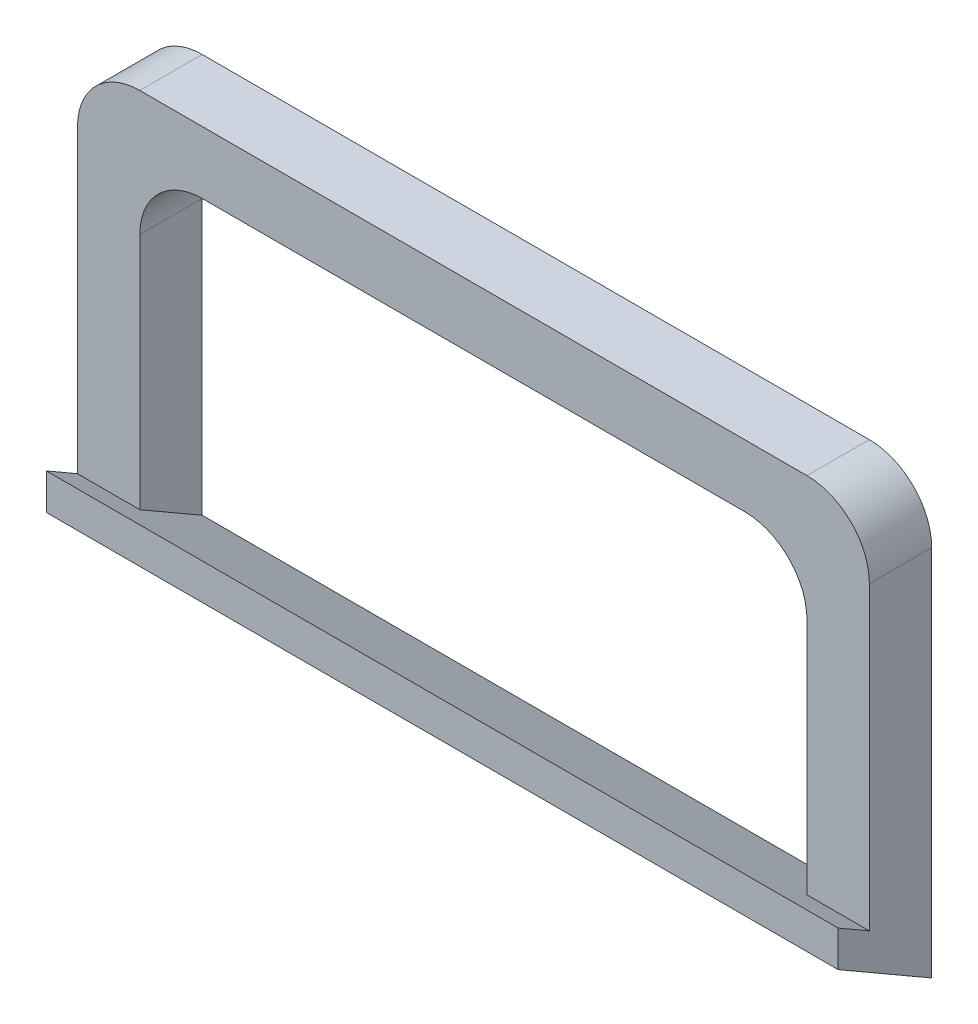
SolidWorks part; units mm, degrees
ref_plane "Alzado" through (0, 0, 0) normal (0, 0, 1) x (1, 0, 0)
ref_plane "Planta" through (0, 0, 0) normal (0, 1, 0) x (1, 0, 0)
ref_plane "Vista lateral" through (0, 0, 0) normal (1, 0, 0) x (0, 0, -1)
sketch "Croquis1" plane through (0, 0, 0) normal (0, 0, 1) x (1, 0, 0)
  line L0 (-36.9312, -5.2517) -> (-36.9312, 48.7483)
  line L1 (-26.9312, 58.7483) -> (80.0688, 58.7483)
  line L2 (90.0688, 48.7483) -> (90.0688, -5.2517)
  line L3 (-36.9312, -5.2517) -> (-26.9312, -5.2517)
  line L4 (-26.9312, -5.2517) -> (-26.9312, 38.7483)
  line L5 (-16.9312, 48.7483) -> (70.0688, 48.7483)
  line L6 (80.0688, 38.7483) -> (80.0688, -5.2517)
  line L7 (80.0688, -5.2517) -> (90.0688, -5.2517)
  arc A0 (-26.9312, 58.7483) -> (-36.9312, 48.7483) centre (-26.9312, 48.7483) ccw
  arc A1 (80.0688, 58.7483) -> (90.0688, 48.7483) centre (80.0688, 48.7483) cw
  arc A2 (-26.9312, 38.7483) -> (-16.9312, 48.7483) centre (-16.9312, 38.7483) cw
  arc A3 (70.0688, 48.7483) -> (80.0688, 38.7483) centre (70.0688, 38.7483) cw
  dimension "D1" = 127
  dimension "D2" = 10
  dimension "D5" = 10
  dimension "D3" = 54
  dimension "D4" = 54
extrude "Saliente-Extruir1" add sketch "Croquis1" along normal blind 10
sketch "Croquis2" plane through (-36.9312, 0, 0) normal (-1, 0, 0) x (0, 0, 1)
  line L0 (0, -11.0252) -> (15, -2.3649)
  line L1 (0, 48.7483) -> (0, -5.2517) construction
  line L2 (0, -11.0252) -> (0, -5.2517)
  line L3 (0, -5.2517) -> (15, 3.4086)
  line L4 (15, 3.4086) -> (15, -2.3649)
  point P1 (2.0096, -9.8649)
  point P4 (0, -11.0345)
  dimension "D1" = 60
  dimension "D3" = 15
extrude "Saliente-Extruir2" add sketch "Croquis2" against normal blind 127
